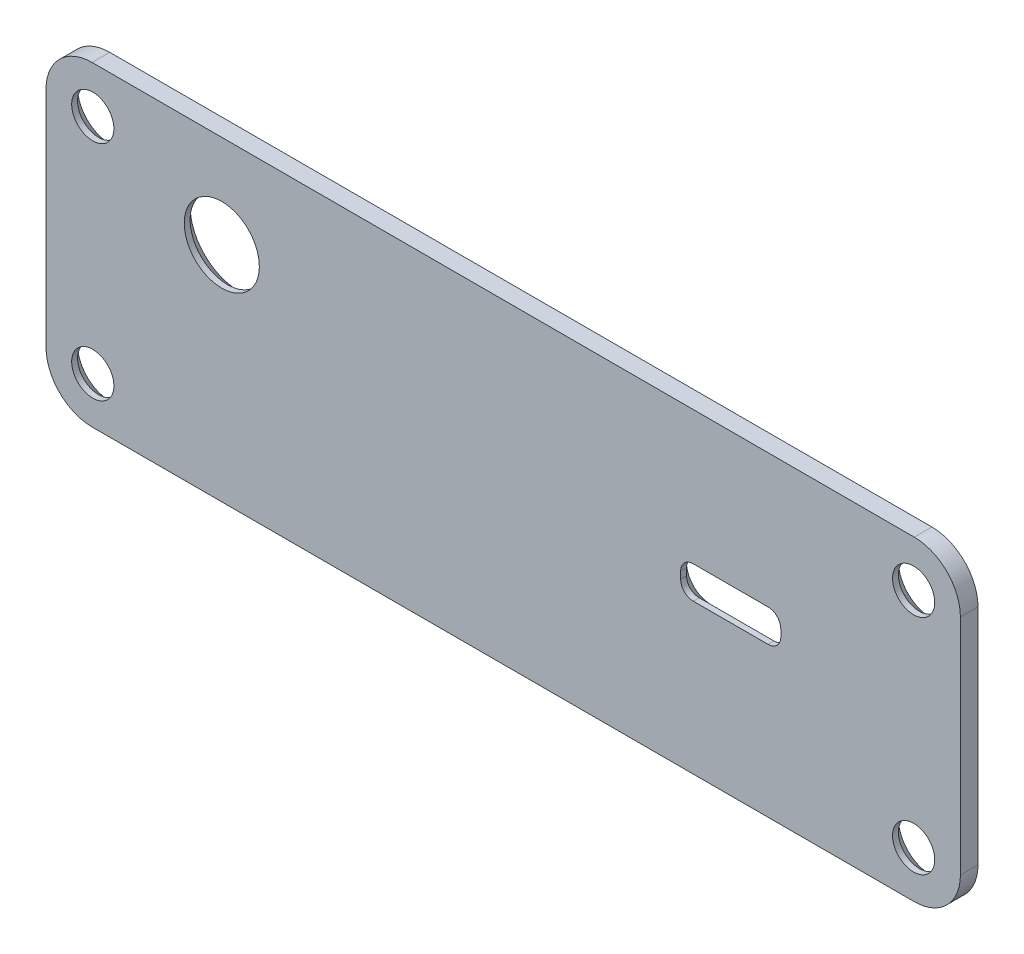
SolidWorks part; units mm, degrees
material "A-Glass Fiber"
ref_plane "Ebene vorne" through (0, 0, 0) normal (0, 0, 1) x (1, 0, 0)
ref_plane "Ebene oben" through (0, 0, 0) normal (0, 1, 0) x (1, 0, 0)
ref_plane "Ebene rechts" through (0, 0, 0) normal (1, 0, 0) x (0, 0, -1)
sketch "Sketch2" plane through (0, 0, 0) normal (0, 0, 1) x (1, 0, 0)
  line L1 (0, 13.462) -> (77.978, 13.462) construction
  line L4 (0, 22.989) -> (0, 3.935)
  line L5 (74.043, 26.924) -> (3.935, 26.924)
  line L6 (77.978, 3.935) -> (77.978, 22.989)
  line L7 (3.935, 0) -> (74.043, 0)
  circle A0 centre (3.989, 22.962) radius 1.8
  circle A1 centre (73.989, 22.962) radius 1.8
  circle A2 centre (3.989, 3.962) radius 1.8
  circle A3 centre (73.989, 3.962) radius 1.8
  arc A4 (0, 3.935) -> (3.935, 0) centre (3.935, 3.935) ccw
  arc A5 (3.935, 26.924) -> (0, 22.989) centre (3.935, 22.989) ccw
  arc A6 (77.978, 22.989) -> (74.043, 26.924) centre (74.043, 22.989) ccw
  arc A7 (74.043, 0) -> (77.978, 3.935) centre (74.043, 3.935) ccw
  circle A8 centre (3.989, 3.962) radius 3.5 construction
  circle A17 centre (3.989, 22.962) radius 3.5 construction
  dimension "D1" = 3.6
  dimension "D19" = 7
  dimension "D23" = 3.935
  dimension "D2" = 70
  dimension "D3" = 19
  dimension "D21" = 26.924
  dimension "D22" = 77.978
extrude "Boss-Extrude2" add sketch "Sketch2" along normal blind 1.5 separate body
sketch "Sketch3" plane through (0, 0, 1.5) normal (0, 0, 1) x (1, 0, 0)
  line L0 (61.58, 12.7718) -> (58.645, 12.7718) construction
  line L1 (58.635, 12.7718) -> (55.2, 12.7718) construction
  line L2 (54.12, 13.8518) -> (54.12, 14.4518) construction
  line L3 (55.2, 15.5318) -> (61.58, 15.5318) construction
  line L12 (62.66, 14.4518) -> (62.66, 13.8518) construction
  line L13 (61.58, 12.7718) -> (58.645, 12.7718)
  line L14 (58.635, 12.7718) -> (55.2, 12.7718)
  line L15 (54.12, 13.8518) -> (54.12, 14.4518)
  line L16 (55.2, 15.5318) -> (61.58, 15.5318)
  line L17 (62.66, 14.4518) -> (62.66, 13.8518)
  line L18 (58.645, 12.7718) -> (58.635, 12.7718)
  spline S0 degree 3 poles (11.79, 18.9845) (11.79, 12.5845) (18.19, 12.5845) (18.19, 18.9845) knots 0 0 0 0 1 1 1 1 weights 1 0.333333 0.333333 1 construction
  spline S1 degree 3 poles (11.79, 18.9845) (11.79, 12.5845) (18.19, 12.5845) (18.19, 18.9845) knots 0 0 0 0 1 1 1 1 weights 1 0.333333 0.333333 1
  spline S2 degree 3 poles (55.2, 15.5318) (54.5673, 15.5318) (54.12, 15.0845) (54.12, 14.4518) knots 0 0 0 0 1 1 1 1 weights 1 0.804738 0.804738 1 construction
  spline S3 degree 3 poles (62.66, 13.8518) (62.66, 13.2192) (62.2126, 12.7718) (61.58, 12.7718) knots 0 0 0 0 1 1 1 1 weights 1 0.804738 0.804738 1 construction
  spline S4 degree 3 poles (55.2, 15.5318) (54.5673, 15.5318) (54.12, 15.0845) (54.12, 14.4518) knots 0 0 0 0 1 1 1 1 weights 1 0.804738 0.804738 1
  spline S5 degree 3 poles (62.66, 13.8518) (62.66, 13.2192) (62.2126, 12.7718) (61.58, 12.7718) knots 0 0 0 0 1 1 1 1 weights 1 0.804738 0.804738 1
  spline S6 degree 3 poles (54.12, 13.8518) (54.12, 13.2192) (54.5673, 12.7718) (55.2, 12.7718) knots 0 0 0 0 1 1 1 1 weights 1 0.804738 0.804738 1 construction
  spline S7 degree 3 poles (61.58, 15.5318) (62.2126, 15.5318) (62.66, 15.0844) (62.66, 14.4518) knots 0 0 0 0 1 1 1 1 weights 1 0.804738 0.804738 1 construction
  spline S8 degree 3 poles (54.12, 13.8518) (54.12, 13.2192) (54.5673, 12.7718) (55.2, 12.7718) knots 0 0 0 0 1 1 1 1 weights 1 0.804738 0.804738 1
  spline S9 degree 3 poles (61.58, 15.5318) (62.2126, 15.5318) (62.66, 15.0844) (62.66, 14.4518) knots 0 0 0 0 1 1 1 1 weights 1 0.804738 0.804738 1
  spline S10 degree 3 poles (18.19, 18.9845) (18.19, 25.3845) (11.79, 25.3845) (11.79, 18.9845) knots 0 0 0 0 1 1 1 1 weights 1 0.333333 0.333333 1 construction
  spline S11 degree 3 poles (18.19, 18.9845) (18.19, 25.3845) (11.79, 25.3845) (11.79, 18.9845) knots 0 0 0 0 1 1 1 1 weights 1 0.333333 0.333333 1
extrude "Cut-Extrude1" cut sketch "Sketch3" against normal blind 10
chamfer "Chamfer1" distance 1 angle 45 13 edges at (75.789, 22.962, 0) (75.789, 3.962, 0) (5.789, 22.962, 0) (5.789, 3.962, 0) (18.19, 18.9845, 0) (58.39, 15.5318, 0) (54.4363, 15.2155, 0) (62.3437, 15.2155, 0) (54.12, 14.1518, 0) (62.66, 14.1518, 0) (54.4363, 13.0881, 0) (62.3437, 13.0881, 0) (58.39, 12.7718, 0)
